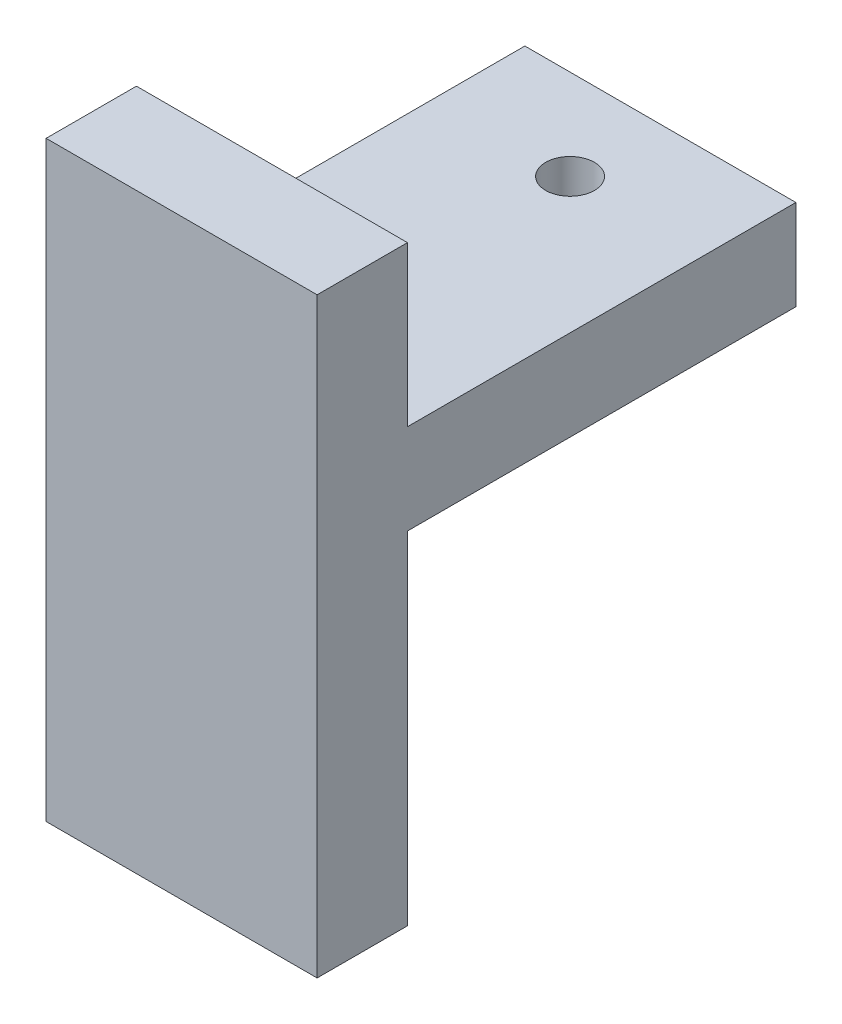
SolidWorks part; units mm, degrees
ref_plane "Front Plane" through (0, 0, 0) normal (0, 0, 1) x (1, 0, 0)
ref_plane "Top Plane" through (0, 0, 0) normal (0, 1, 0) x (1, 0, 0)
ref_plane "Right Plane" through (0, 0, 0) normal (1, 0, 0) x (0, 0, -1)
sketch "Sketch1" plane through (0, 0, 0) normal (0, 1, 0) x (1, 0, 0)
  line L1 (-15, -26.5) -> (15, -26.5)
  line L2 (-15, -26.5) -> (-15, 26.5)
  line L3 (-15, 26.5) -> (15, 26.5)
  line L4 (15, -26.5) -> (15, 26.5)
  line L5 (-15, -26.5) -> (15, 26.5) construction
  line L6 (-15, 26.5) -> (15, -26.5) construction
  circle A0 centre (0, 16.5) radius 2.7
  point P0 (0, 0)
  dimension "D5" = 5.4
  dimension "D1" = 30
  dimension "D2" = 53
  dimension "D3" = 10
  dimension "D4" = 15
extrude "Boss-Extrude1" add sketch "Sketch1" along normal blind 10
sketch "Sketch3" plane through (0, 10, 0) normal (0, 1, 0) x (1, 0, 0)
  line L0 (-15, 26.5) -> (-15, -26.5) construction
  line L1 (15, -26.5) -> (-15, -26.5)
  line L2 (15, -26.5) -> (15, -16.5)
  line L3 (15, -16.5) -> (-15, -16.5)
  line L4 (-15, -26.5) -> (-15, -16.5)
  dimension "D1" = 10
extrude "Boss-Extrude2" add sketch "Sketch3" along normal blind 17.65
sketch "Sketch5" plane through (0, 0, 0) normal (0, -1, 0) x (1, 0, 0)
  line L0 (15, 26.5) -> (15, -26.5) construction
  line L1 (-15, 26.5) -> (15, 26.5)
  line L2 (-15, 26.5) -> (-15, 16.5)
  line L3 (-15, 16.5) -> (15, 16.5)
  line L4 (15, 26.5) -> (15, 16.5)
  dimension "D1" = 10
extrude "Boss-Extrude4" add sketch "Sketch5" along normal blind 37.85
